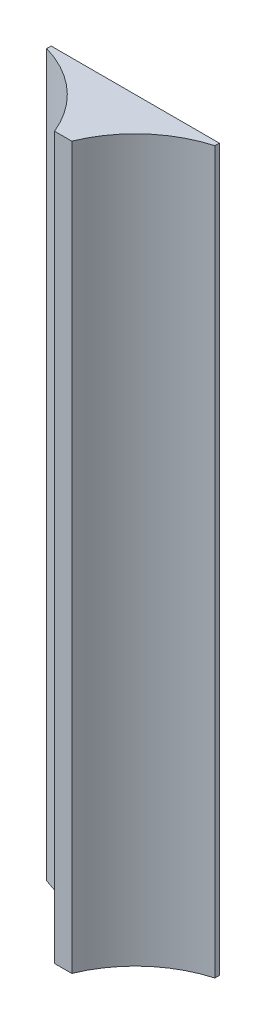
SolidWorks part; units mm, degrees
ref_plane "Front" through (0, 0, 0) normal (0, 0, 1) x (1, 0, 0)
ref_plane "Top" through (0, 0, 0) normal (0, 1, 0) x (1, 0, 0)
ref_plane "Right" through (0, 0, 0) normal (1, 0, 0) x (0, 0, -1)
sketch "Sketch1" plane through (0, 0, 0) normal (0, 1, 0) x (1, 0, 0)
  line L0 (-0.7169, 0) -> (0.7169, 0)
  line L1 (7, 5.629) -> (7, 6)
  line L2 (7, 6) -> (-7, 6)
  line L3 (-7, 6) -> (-7, 5.629)
  arc A0 (0.7169, 0) -> (7, 5.629) centre (9.65, -3.65) cw
  arc A1 (-7, 5.629) -> (-0.7169, 0) centre (-9.65, -3.65) cw
  point P9 (0, 6)
  point P10 (0, 0)
  dimension "D1" = 9.65
  dimension "D6" = 6
  dimension "D2" = 19.3
  dimension "D3" = 9.65
  dimension "D4" = 14
extrude "Boss-Extrude1" add sketch "Sketch1" along normal blind 60
sketch "Sketch3" plane through (0, 0, -6) normal (0, 0, -1) x (-1, 0, 0)
  line L0 (0, 0) -> (0, 60) construction
  line L1 (-7, 0) -> (7, 0) construction
  line L2 (-7, 60) -> (7, 60) construction
  point P6 (0, 45)
  point P7 (0, 15)
  dimension "D1" = 15
  dimension "D2" = 15
